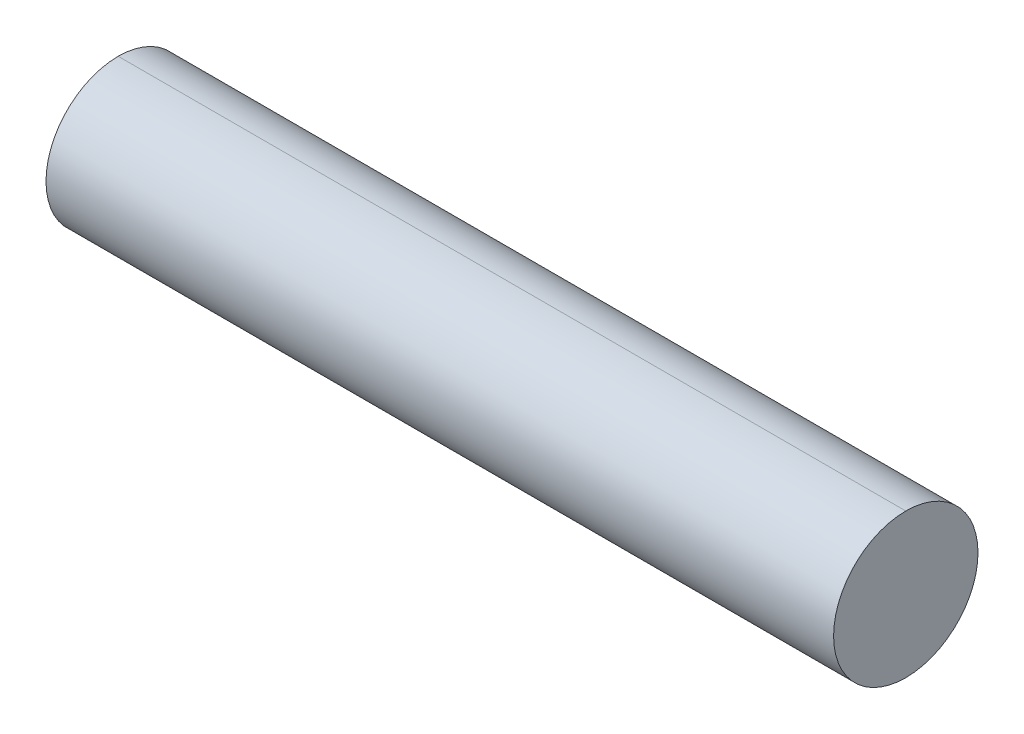
SolidWorks part; units mm, degrees
material "AISI 4340 Steel, normalized"
ref_plane "Front Plane" through (0, 0, 0) normal (0, 0, 1) x (1, 0, 0)
ref_plane "Top Plane" through (0, 0, 0) normal (0, 1, 0) x (1, 0, 0)
ref_plane "Right Plane" through (0, 0, 0) normal (1, 0, 0) x (0, 0, -1)
sketch "Sketch1" plane through (0, 0, 0) normal (1, 0, 0) x (0, 0, -1)
  circle A0 centre (0, 0) radius 19.05
  dimension "D1" = 38.1
extrude "Boss-Extrude1" add sketch "Sketch1" along normal blind 228.6
split line "Split Line1"
sketch "Sketch2" plane through (0, 0, 0) normal (-1, 0, 0) x (0, 0, 1)
  arc A4 (0, -19.05) -> (0, 19.05) centre (0, 0) ccw
  arc A5 (0, 19.05) -> (0, -19.05) centre (0, 0) ccw
  arc A6 (0, -19.05) -> (0, 19.05) centre (0, 0) ccw
  arc A7 (0, 19.05) -> (0, -19.05) centre (0, 0) ccw
  dimension "D1" = 0
extrude "Cut-Extrude1" cut sketch "Sketch2" against normal up to surface (20.8 mm away)
